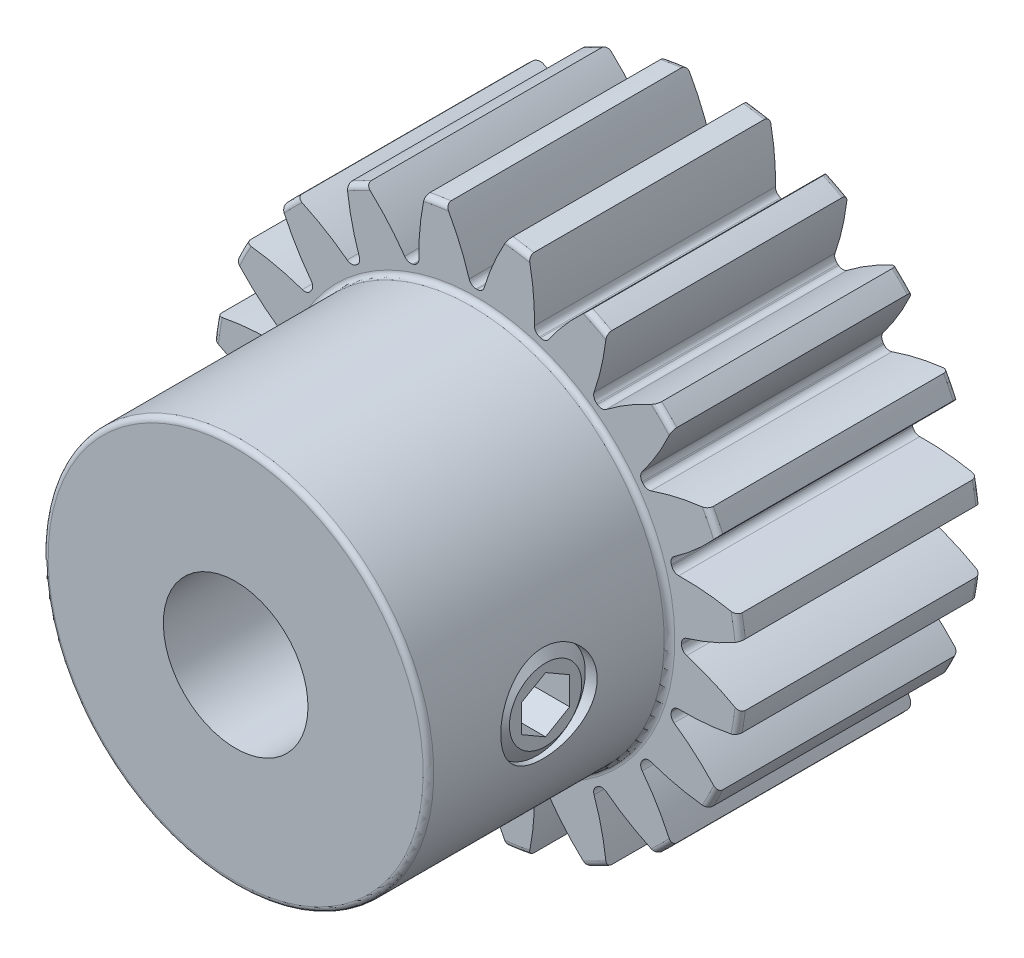
SolidWorks part; units mm, degrees
ref_plane "Front Plane" through (0, 0, 0) normal (0, 0, 1) x (1, 0, 0)
ref_plane "Top Plane" through (0, 0, 0) normal (0, 1, 0) x (1, 0, 0)
ref_plane "Right Plane" through (0, 0, 0) normal (1, 0, 0) x (0, 0, -1)
sketch "Sketch1" plane through (0, 0, 0) normal (0, 0, 1) x (1, 0, 0)
  line L0 (-254, 0) -> (254, 0) construction
  line L1 (0, 0) -> (0, 3) construction
  line L2 (-2, 2.2361) -> (-2, 4.8) construction
  line L3 (-2, 4.8) -> (2, 4.8) construction
  line L4 (2, 4.8) -> (2, 2.2361) construction
  line L5 (0, 3) -> (0, 4.8) construction
  line L6 (-7.8581, -1.5) -> (-7.8581, 1.5)
  line L7 (-7.8581, 1.5) -> (-7.508, 2)
  line L8 (-7.508, 2) -> (-4.7622, 2)
  line L9 (-4.7622, 2) -> (-3.8581, 1.0959)
  line L10 (-3.8581, 1.0959) -> (-4.5166, 0)
  line L11 (-3.8581, -1.0959) -> (-4.5166, 0)
  line L12 (-4.7622, -2) -> (-3.8581, -1.0959)
  line L13 (-7.508, -2) -> (-4.7622, -2)
  line L14 (-7.8581, -1.5) -> (-7.508, -2)
  circle A0 centre (0, 0) radius 11 construction
  circle A1 centre (0, 0) radius 10 construction
  circle A2 centre (0, 0) radius 8.5 construction
  circle A3 centre (0, 0) radius 8 construction
  circle A4 centre (0, 0) radius 3 construction
  point P25 (-7.8581, 0)
  dimension "D2" = 1
  dimension "D3" = 2.5
  dimension "D1" = 2.5
  dimension "D4" = 35
  dimension "D6" = 4
  dimension "D7" = 3
  dimension "D8" = 45
  dimension "D9" = 118
sketch "Sketch2" plane through (0, 0, 0) normal (1, 0, 0) x (0, 0, -1)
  line L0 (0, 0) -> (-10, 0) construction
  line L1 (-10, 0) -> (-20, 0) construction
  line L3 (-15, 1.1547) -> (-16, 0.5774)
  line L4 (-16, 0.5774) -> (-16, -0.5774)
  line L5 (-16, -0.5774) -> (-15, -1.1547)
  line L6 (-15, -1.1547) -> (-14, -0.5774)
  line L7 (-14, -0.5774) -> (-14, 0.5774)
  line L8 (-14, 0.5774) -> (-15, 1.1547)
  circle A0 centre (-15, 0) radius 2
  circle A1 centre (-15, 0) radius 1 construction
  dimension "D2" = 4
  dimension "D1" = 2
sketch "Sketch4" plane through (0, 0, 0) normal (1, 0, 0) x (0, 0, -1)
  line L0 (-20, 3) -> (-20, 8)
  line L1 (-20, 8) -> (-10, 8)
  line L2 (-10, 8) -> (-10, 11)
  line L3 (-10, 11) -> (0, 11)
  line L4 (0, 11) -> (0, 3)
  line L5 (-10, 8) -> (-10, 0) construction
  line L6 (0, 11) -> (0, -11) construction
  line L7 (-10, 8) -> (0, 8) construction
  line L12 (-20, 3) -> (0, 3)
revolve "Revolve1" add sketch "Sketch4" angle 360 about L1
fillet "Fillet2" radius 0.22 4 edges at (0, 8, 20) (0, 8, 10) (0, 11, 10) (0, 11, 0)
sketch "Sketch7" plane through (0, 0, 10) normal (0, 0, 1) x (1, 0, 0)
  line L0 (0, 0) -> (0, 11) construction
  line L1 (0.7846, 9.9692) -> (1.2233, 10.9318) construction
  line L3 (1.7208, 10.8646) -> (1.5643, 9.8769) construction
  line L4 (1.5643, 9.8769) -> (1.3297, 8.3954) construction
  line L5 (0, 0) -> (1.3297, 8.3954) construction
  line L6 (0.7846, 9.9692) -> (0, 0) construction
  line L7 (0.7846, 9.9692) -> (0.863, 10.9661) construction
  line L8 (0.7846, 9.9692) -> (0, 0) construction
  circle A0 centre (0, 0) radius 11 construction
  arc A1 (-0.0232, 8.5) -> (0.0232, 8.5) centre (0, 0) cw
  circle A2 centre (0, 0) radius 8.5 construction
  arc A3 (-0.7846, 9.9692) -> (0.7846, 9.9692) centre (0, 0) cw construction
  circle A4 centre (0, 0) radius 10 construction
  arc A5 (2.1548, 10.7869) -> (1.284, 10.9248) centre (0, 0) ccw construction
  arc A6 (0.7846, 9.9692) -> (2.3345, 9.7237) centre (0, 0) cw construction
  arc A7 (-1.284, 10.9248) -> (1.284, 10.9248) centre (0, 0) cw
  arc A8 (0.3112, 8.7133) -> (1.284, 10.9248) centre (9.8842, 5.8222) cw
  arc A9 (-0.3112, 8.7133) -> (-1.284, 10.9248) centre (-9.8842, 5.8222) ccw
  arc A10 (-0.0232, 8.5) -> (-0.3112, 8.7133) centre (-0.024, 8.8) cw
  arc A11 (0.0232, 8.5) -> (0.3112, 8.7133) centre (0.024, 8.8) ccw
  point P26 (-0.2484, 8.4964)
  point P29 (0.2484, 8.4964)
  dimension "D4" = 0.3
  dimension "D5" = 10
  dimension "D3" = 20
  dimension "D1" = 3.1416
  dimension "D2" = 1.5708
extrude "Cut-Extrude2" cut sketch "Sketch7" against normal through all
pattern_circular "CirPattern1" count 20 over 360 about axis through (0, 0, 0) along (0, 0, 1) of "Cut-Extrude2"
ref_plane "Plane1" through (8, 0, 0) normal (1, 0, 0) x (0, 0, -1)
sketch "Sketch11" plane through (8, 0, 0) normal (1, 0, 0) x (0, 0, -1)
  circle A0 centre (-15, 0) radius 2 construction
  circle A1 centre (-15, 0) radius 2
extrude "Cut-Extrude3" cut sketch "Sketch11" against normal up to vertex up to point (0, 0, 15)
ref_plane "Plane2" through (0, 0, 15) normal (0, 0, 1) x (1, 0, 0)
sketch "Sketch13" plane through (0, 0, 15) normal (0, 0, 1) x (1, 0, 0)
  line L0 (-7.508, 2) -> (-4.7622, 2) construction
  line L1 (-4.7622, 2) -> (-3.8581, 1.0959) construction
  line L2 (-3.8581, 1.0959) -> (-4.5166, 0) construction
  line L3 (-7.8581, 1.5) -> (-7.508, 2) construction
  line L4 (-7.508, 2) -> (-4.7622, 2) construction
  line L5 (-4.7622, 2) -> (-3.8581, 1.0959) construction
  line L6 (-3.8581, 1.0959) -> (-4.5166, 0) construction
  line L7 (-7.8581, 1.5) -> (-7.508, 2) construction
  line L8 (-7.8581, 1.5) -> (-7.8581, 0) construction
  line L9 (-7.8581, 0) -> (-4.5166, 0) construction
  line L10 (0, 7.78) -> (0, -7.78) construction
  line L11 (7.8581, 0) -> (4.5166, 0)
  line L12 (7.8581, 1.5) -> (7.8581, 0)
  line L13 (7.8581, 1.5) -> (7.508, 2)
  line L14 (3.8581, 1.0959) -> (4.5166, 0)
  line L15 (4.7622, 2) -> (3.8581, 1.0959)
  line L16 (7.508, 2) -> (4.7622, 2)
  circle A0 centre (0, 0) radius 7.78 construction
revolve "Revolve2" add sketch "Sketch13" angle 360 about L9
sketch "Sketch14" plane through (7.8581, 0, 0) normal (-1, 0, 0) x (0, 0, 1)
  line L0 (14, -0.5774) -> (14, 0.5774) construction
  line L1 (14, 0.5774) -> (15, 1.1547) construction
  line L2 (15, 1.1547) -> (16, 0.5774) construction
  line L3 (16, 0.5774) -> (16, -0.5774) construction
  line L4 (16, -0.5774) -> (15, -1.1547) construction
  line L5 (15, -1.1547) -> (14, -0.5774) construction
  line L6 (14, -0.5774) -> (14, 0.5774)
  line L7 (14, 0.5774) -> (15, 1.1547)
  line L8 (15, 1.1547) -> (16, 0.5774)
  line L9 (16, 0.5774) -> (16, -0.5774)
  line L10 (16, -0.5774) -> (15, -1.1547)
  line L11 (15, -1.1547) -> (14, -0.5774)
extrude "Cut-Extrude5" cut sketch "Sketch14" along normal blind 1.5
sketch "Sketch12" [suppressed] plane through (0, 0, 25) normal (0, 0, 1) x (1, 0, 0)
  line L0 (0, 0) -> (0, 6) construction
  line L1 (-2, 5.6569) -> (-2, 7.8) construction
  line L2 (-1.0506, 51.72) -> (1.0506, 51.72)
  line L3 (-2, 7.8) -> (2, 7.8) construction
  line L4 (2, 7.8) -> (2, 5.6569) construction
  line L5 (-2, 5.6569) -> (-2, 7.8)
  line L6 (-2, 7.8) -> (2, 7.8)
  line L7 (2, 7.8) -> (2, 5.6569)
  arc A0 (-2, 5.6569) -> (2, 5.6569) centre (0, 0) cw
  circle M2 centre (0, 0) radius 6
extrude "Cut-Extrude4" [suppressed] cut sketch "Sketch12" against normal through all contours L7 L6 L5 A0 M2
pattern_circular "CirPattern2" [suppressed] count 2 over 90
sketch "Sketch15" plane through (0, 0, 0) normal (0, 0, -1) x (-1, 0, 0)
  circle A0 centre (0, 0) radius 10 construction
  dimension "D1" = 20
ref_plane "Plane3" through (0, 0, 5.08) normal (0, 0, -1) x (-1, 0, 0)
sketch "Sketch17" plane through (0, 0, 5.08) normal (0, 0, -1) x (-1, 0, 0)
  circle A0 centre (0, 0) radius 10.7989 construction
  circle A1 centre (0, 0) radius 7.78 construction
equation "\"D1@Sketch1\"=2.5*(\"Pitch Dia.@Sketch1\"/\"Number of Teeth@Sketch1\")"
equation "\"D1@CirPattern1\"=\"Number of Teeth@Sketch1\""
equation "\"D1@Fillet2\"=\"OD@Sketch1\"*.01"
equation "\"D1@Sketch7\"=3.14159*(\"Pitch Dia.@Sketch1\"/\"Number of Teeth@Sketch1\")"
equation "\"D2@Sketch7\"=\"D1@Sketch7\"/2"
equation "\"D4@Sketch7\"=\"D1@Sketch7\"*.0955"
equation "\"D5@Sketch7\"=\"Pitch Dia.@Sketch1\"/2"
equation "\"D7@Sketch1\"=\"Set Screw Dia@Sketch1\"-1mm"
equation "\"D2@Sketch2\"=\"Set Screw Dia@Sketch1\""
